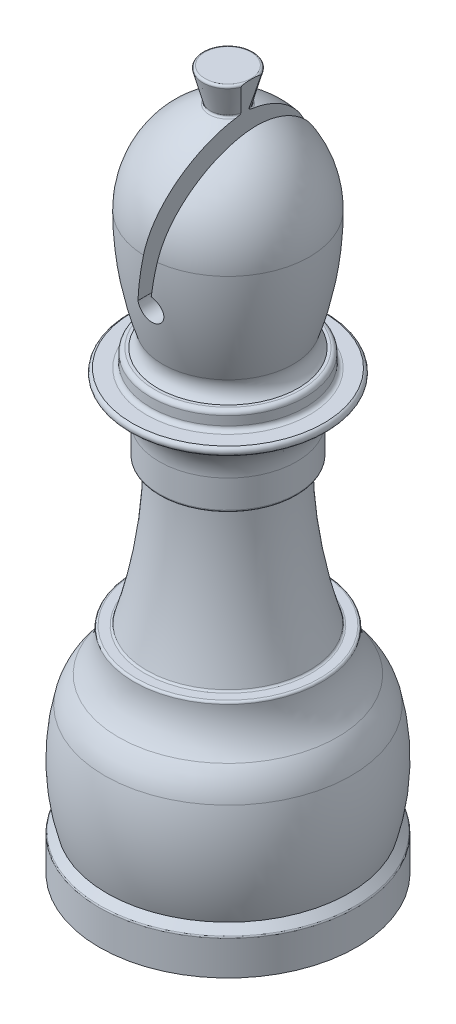
SolidWorks part; units mm, degrees
ref_plane "Front Plane" through (0, 0, 0) normal (0, 0, 1) x (1, 0, 0)
ref_plane "Top Plane" through (0, 0, 0) normal (0, 1, 0) x (1, 0, 0)
ref_plane "Right Plane" through (0, 0, 0) normal (1, 0, 0) x (0, 0, -1)
sketch "Sketch1" plane through (0, 0, 0) normal (0, 0, 1) x (1, 0, 0)
  line L0 (0, 81.5) -> (-2.6742, 81.5)
  line L1 (-15, 4) -> (-15, 0)
  line L2 (-14.1036, 5) -> (-14.9268, 4.1768)
  line L3 (-2.0398, 77.9166) -> (-2.9157, 81.1853)
  line L4 (-9, 51.4698) -> (-9, 52.5)
  line L5 (-8, 42.25) -> (-8, 45.5)
  line L6 (0, 81.5) -> (0, 0)
  line L7 (0, 0) -> (-15, 0)
  line L8 (-8.5, 53) -> (-8.1771, 53)
  line L9 (-9.5, 50.9698) -> (-11.1711, 50.9698)
  line L10 (-7.25, 42) -> (-7.75, 42)
  line L11 (-9.7092, 25) -> (-10.7092, 25)
  line L12 (0, 0) -> (0, -6.9862) construction
  line L13 (-2.9157, 81.1853) -> (-3, 81.5) construction
  line L14 (-3, 81.5) -> (-2.6742, 81.5) construction
  line L15 (-10.9592, 24.75) -> (-10.9592, 25.4702) construction
  arc A0 (-14.9268, 4.1768) -> (-15, 4) centre (-14.75, 4) ccw
  arc A1 (-14.3628, 16.9916) -> (-14.1036, 5) centre (9, 11.4981) ccw
  arc A3 (-10.7092, 25) -> (-10.9592, 24.75) centre (-10.7092, 24.75) ccw
  arc A4 (-9.7092, 25) -> (-9.4697, 25.1781) centre (-9.7092, 25.25) ccw
  arc A5 (-2.6742, 81.5) -> (-2.9157, 81.1853) centre (-2.6742, 81.25) ccw
  arc A6 (-2.1902, 77.6191) -> (-2.0398, 77.9166) centre (-2.2813, 77.8519) ccw
  arc A7 (-2.1902, 77.6191) -> (-9.5, 66.9097) centre (2, 66.9097) ccw
  arc A8 (-9.5, 66.9097) -> (-7.6013, 55.1283) centre (28, 66.9097) ccw
  arc A9 (-8.1771, 53) -> (-7.6013, 55.1283) centre (-9.5, 54.5) ccw
  arc A10 (-8.5, 53) -> (-9, 52.5) centre (-8.5, 52.5) ccw
  arc A11 (-9.5, 50.9698) -> (-9, 51.4698) centre (-9.5, 51.4698) ccw
  arc A12 (-11.1711, 50.9698) -> (-11.1711, 50.0302) centre (-11, 50.5) ccw
  arc A13 (-8, 45.5) -> (-11.1711, 50.0302) centre (-12.8214, 45.5) ccw
  arc A14 (-8, 42.25) -> (-7.75, 42) centre (-7.75, 42.25) ccw
  arc A15 (-7, 41.7489) -> (-7.25, 42) centre (-7.25, 41.75) ccw
  arc A16 (-9.4697, 25.1781) -> (-7, 41.7489) centre (-65.5114, 42) ccw
  arc A17 (-12.7539, 20.0697) -> (-10.9592, 24.75) centre (-17.9592, 24.75) ccw
  arc A18 (-12.7539, 20.0697) -> (-14.3628, 16.9916) centre (-7.5487, 15.3893) ccw
  dimension "D3" = 0.25
  dimension "D4" = 25
  dimension "D5" = 1
  dimension "D6" = 11.5
  dimension "D7" = 37.5
  dimension "D8" = 2
  dimension "D9" = 0.5
  dimension "D10" = 0.5
  dimension "D11" = 3
  dimension "D12" = 42
  dimension "D17" = 9.5
  dimension "D25" = 15
  dimension "D27" = 24
  dimension "D31" = 7
  dimension "D16" = 7
  dimension "D2" = 81.5
  dimension "D13" = 15
  dimension "D14" = 28
  dimension "D15" = 0.5
  dimension "D18" = 42
  dimension "D19" = 8
  dimension "D20" = 50.5
  dimension "D21" = 9
  dimension "D22" = 53
  dimension "D23" = 54.5
  dimension "D24" = 2
  dimension "D26" = 3
  dimension "D28" = 5
  dimension "D29" = 45.5
  dimension "D30" = 135
  dimension "D32" = 4
revolve "Revolve1" add sketch "Sketch1" angle 360 about L12
sketch "Sketch2" plane through (0, 0, 0) normal (0, 0, 1) x (1, 0, 0)
  line L0 (0.9164, 65.6538) -> (0.3439, 62.9601)
  line L1 (-1.5, 61.5) -> (-0.5901, 65.7807)
  line L2 (3.3474, 77.0908) -> (0.9164, 65.6538)
  line L3 (-0.5901, 65.7807) -> (1.9459, 77.7115)
  line L4 (1.9459, 77.7115) -> (2.7775, 81.6241)
  line L5 (2.7775, 81.6241) -> (4.2447, 81.3123)
  line L6 (4.2447, 81.3123) -> (3.3474, 77.0908)
  line L7 (0, 61.1245) -> (0, 78.4799) construction
  line L8 (0, 61.5) -> (0, 81.5) construction
  line L9 (0, 61.5) -> (0, 0) construction
  arc A0 (-1.5, 61.5) -> (0.3439, 62.9601) centre (0, 61.5) ccw
  arc A1 (9.5, 66.9097) -> (2.1902, 77.6191) centre (-2, 66.9097) ccw construction
  point P6 (0, 81.5)
  dimension "D2" = 1.5
  dimension "D1" = 12
  dimension "D3" = 20
  dimension "D4" = 1.5
  dimension "D5" = 61.5
  dimension "D6" = 4
extrude "Cut-Extrude1" cut sketch "Sketch2" against normal through all both and the other way through all
scale "Scale1" scale about origin uniform scaling yes scale factor 0.766667
sketch "Sketch3" plane through (0, 0, 0) normal (0, -1, 0) x (1, 0, 0)
  circle A0 centre (0, 0) radius 10.2
  dimension "D1" = 20.4
extrude "Cut-Extrude2" cut sketch "Sketch3" against normal blind 7 and the other way through all
sketch "Sketch4" plane through (0, 0, 0) normal (0, -1, 0) x (1, 0, 0)
  circle A0 centre (0, 0) radius 9.15
  circle A1 centre (0, 0) radius 10.2 construction
  circle A2 centre (0, 0) radius 10.2
  dimension "D1" = 18.3
sketch "Sketch5" plane through (0, 0, 0) normal (0, 0, 1) x (1, 0, 0)
  line L0 (10.8127, 3.8333) -> (10.8127, 14.5602) construction
  line L1 (10.8127, 3.8333) -> (-10.8127, 3.8333) construction
sketch "Sketch6" plane through (0, 0, 0) normal (0, 0, 1) x (1, 0, 0)
  line L0 (-10.75, 1) -> (0, 1)
  line L1 (-10.75, 1) -> (-10.75, 0)
  line L2 (-10.75, 0) -> (0, 0)
  line L3 (0, 0) -> (0, -1) construction
  line L4 (0, 0) -> (0, 1)
  point P0 (5.375, 0.75)
  point P4 (-6.925, 0)
  dimension "D1" = 12.3
  dimension "D2" = 1
  dimension "D3" = 3.825
  dimension "D4" = 21.5
revolve "Cut-Revolve1" cut sketch "Sketch6" angle 360 about L3
sketch "Sketch7" plane through (0, 0, 0) normal (0, 0, 1) x (1, 0, 0)
  line L0 (0, 0) -> (0, -0.9422) construction
  line L1 (0, 1.0046) -> (0, 3.5)
  line L2 (0, 3.5) -> (-10, 3.5)
  line L3 (-10.55, 0) -> (0, 0)
  line L4 (-10.55, 1) -> (-10.55, 0)
  line L5 (-10, 1) -> (-10.55, 1)
  line L6 (0, 0) -> (0, 1.0046)
  line L7 (-10, 1) -> (-10, 3.5)
  line L8 (-10.75, 0) -> (10.75, 0) construction
  dimension "D1" = 3.5
  dimension "D2" = 20
  dimension "D3" = 21.1
  dimension "D4" = 1
revolve "Base (Black Bishop)" [suppressed] add sketch "Sketch7" angle 360 about L0
sketch "Sketch8" plane through (0, 0, 0) normal (0, 0, 1) x (1, 0, 0)
  line L0 (0, 0) -> (0, -2.2211) construction
  line L1 (0, 0) -> (0, 4.5)
  line L2 (0, 4.5) -> (-10, 4.5)
  line L3 (-10.55, 0) -> (0, 0)
  line L4 (-10.55, 1) -> (-10.55, 0)
  line L5 (-10, 1) -> (-10.55, 1)
  line L7 (-10, 1) -> (-10, 4.5)
  dimension "D2" = 20
  dimension "D3" = 1
  dimension "D4" = 21.1
  dimension "D1" = 4.5
revolve "Base (White Bishop)" add sketch "Sketch8" angle 360 about L0
equation "\"D1@Sketch3\"=20.4mm"
equation "\"D1@Cut-Extrude2\"=1mm + 6mm"
equation "\"D1@Sketch4\"=\"WeightOuterDiam\"+0.3mm"
equation "\"D1\"= \"WeightHeight\""
equation "\"D1@Cut-Extrude3\"=\"QueenHeight\"+\"MagThickness\"-\"FeltThickness\""
equation "\"D1@Sketch2\"=\"MagDiam\""
equation "\"D1@Cut-Extrude1\"=\"QueenHeight\"+\"MagThickness\""
equation "\"MagDiam\"= 12mm"
equation "\"D1@Sketch6\"=\"MagDiam\"+0.3"
equation "\"D1@Sketch7\"=3.5mm"
equation "\"D1@Cut-Extrude4\"=\"SocketDepth\""
equation "\"D1@Sketch8\"=4.5mm"
equation "\"D1@Cut-Extrude5\"=\"ThreadedDepth\"+3mm"
equation "\"PawnHeight\"= 1mm"
equation "\"MagThickness\"= 3mm"
equation "\"KnightHeight\"= 2.5mm"
equation "\"RookHeight\"= 4mm"
equation "\"BishopHeight\"= 5.5mm"
equation "\"QueenHeight\"= 6.5mm"
equation "\"KingHeight\"= 8mm"
equation "\"WeightOuterDiam\"= 18mm"
equation "\"WeightInnerDiam\"= \"MagDiam\" + 0.3mm"
equation "\"WeightHeight\"= 9mm"
equation "\"BaseOuterDiam\"= 20mm"
equation "\"BaseInnerDiam\"= 12.7mm"
equation "\"FeltThickness\"= 1mm"
equation "\"ThreadedDepth\"= 10mm"
equation "\"TapdrillDiam\"= 4.4mm"
equation "\"SocketDepth\"= 5mm"
equation "\"SocketDiam\"= 8.5mm"
equation "\"D1@Sketch5\"=\"SocketDiam\"+0.3"
equation "\"D1@Cut-Extrude6\"=\"ThreadedDepth\"+3mm"
